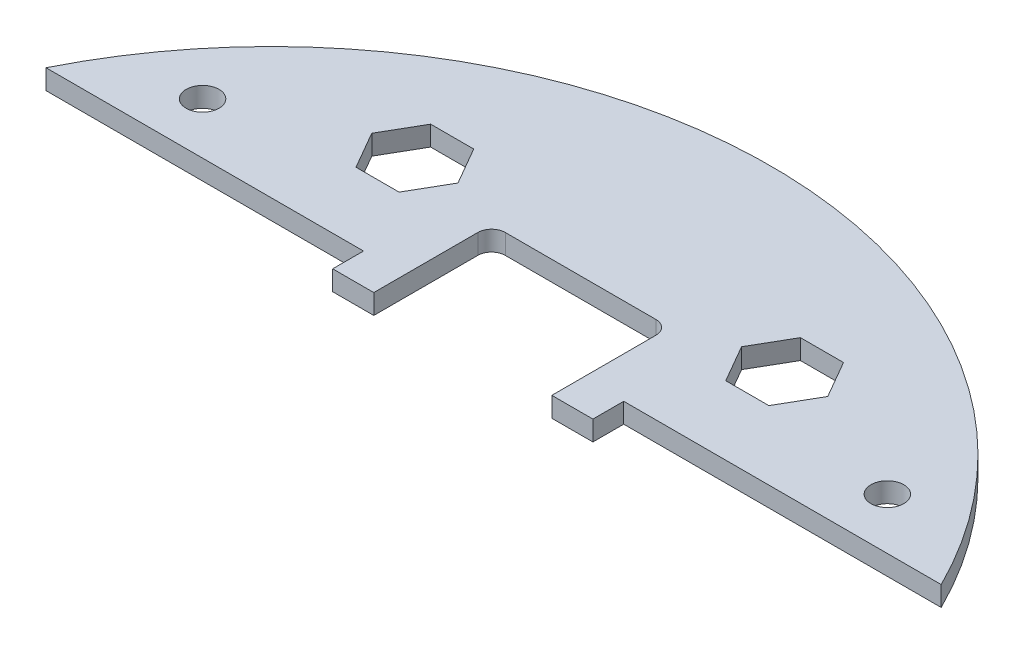
SolidWorks part; units mm, degrees
material "Acrylic (Medium-high impact)"
ref_plane "Front Plane" through (0, 0, 0) normal (0, 0, 1) x (1, 0, 0)
ref_plane "Top Plane" through (0, 0, 0) normal (0, 1, 0) x (1, 0, 0)
ref_plane "Right Plane" through (0, 0, 0) normal (1, 0, 0) x (0, 0, -1)
sketch "Sketch1" plane through (0, 0, 0) normal (0, 1, 0) x (1, 0, 0)
  line L0 (0, -85) -> (-32.7511, -65.2408) construction
  line L1 (0, -85) -> (0, 0) construction
  arc A0 (36.8566, -63.0126) -> (-36.8566, -63.0126) centre (0, 0) ccw
  arc A1 (30.3631, -61.7375) -> (-30.3631, -61.7375) centre (0, -85) ccw
  arc A2 (36.8566, -63.0126) -> (30.3631, -61.7375) centre (34.3322, -58.6967) cw
  arc A3 (-30.3631, -61.7375) -> (-36.8566, -63.0126) centre (-34.3322, -58.6967) cw
  dimension "D1" = 146
  dimension "D2" = 76.5
  dimension "D4" = 5
  dimension "D3" = 85
extrude "Boss-Extrude1" add sketch "Sketch1" along normal blind 2.9
sketch "solenoid placement" plane through (0, 2.9, 0) normal (0, 1, 0) x (1, 0, 0)
  line L4 (-19, -36) -> (19, -36)
  line L5 (-19, 28) -> (-19, -36)
  line L6 (19, 28) -> (-19, 28)
  line L7 (19, -36) -> (19, 28)
  line L8 (-19, -36) -> (19, -36)
  line L9 (-19, 28) -> (-19, -36)
  line L10 (19, 28) -> (-19, 28)
  line L11 (19, -36) -> (19, 28)
  dimension "D1" = 0
extrude "Cut-Extrude1" cut sketch "solenoid placement" against normal through all
sketch "Sketch4" plane through (0, 2.9, 0) normal (0, 1, 0) x (1, 0, 0)
  line L6 (-13, 28) -> (13, 28)
  line L7 (13, 28) -> (13, 43.2)
  line L8 (11, 45.2) -> (-11, 45.2)
  line L9 (-13, 43.2) -> (-13, 28)
  line L10 (-13, 28) -> (13, 28)
  line L11 (13, 28) -> (13, 43.2)
  line L12 (11, 45.2) -> (-11, 45.2)
  line L13 (-13, 43.2) -> (-13, 28)
  arc A4 (13, 43.2) -> (11, 45.2) centre (11, 43.2) ccw
  arc A5 (13, 43.2) -> (11, 45.2) centre (11, 43.2) ccw
  arc A6 (-11, 45.2) -> (-13, 43.2) centre (-11, 43.2) ccw
  arc A7 (-11, 45.2) -> (-13, 43.2) centre (-11, 43.2) ccw
  dimension "D1" = 0
extrude "Cut-Extrude4" cut sketch "Sketch4" against normal through all
sketch "Sketch5" plane through (0, 2.9, 0) normal (0, 1, 0) x (1, 0, 0)
  line L0 (0, 0) -> (0, 73) construction
  line L1 (-20.7069, 48) -> (-23.8534, 53.45)
  line L2 (-23.8534, 53.45) -> (-30.1466, 53.45)
  line L3 (-30.1466, 53.45) -> (-33.2931, 48)
  line L4 (-33.2931, 48) -> (-30.1466, 42.55)
  line L5 (-30.1466, 42.55) -> (-23.8534, 42.55)
  line L6 (-23.8534, 42.55) -> (-20.7069, 48)
  line L7 (23.8534, 42.55) -> (20.7069, 48)
  line L8 (30.1466, 42.55) -> (23.8534, 42.55)
  line L9 (33.2931, 48) -> (30.1466, 42.55)
  line L10 (30.1466, 53.45) -> (33.2931, 48)
  line L11 (23.8534, 53.45) -> (30.1466, 53.45)
  line L12 (20.7069, 48) -> (23.8534, 53.45)
  circle A0 centre (-27, 48) radius 5.45 construction
  circle A2 centre (27, 48) radius 5.45 construction
  arc A3 (36.8566, -63.0126) -> (-36.8566, -63.0126) centre (0, 0) ccw construction
  dimension "D3" = 10.9
extrude "Cut-Extrude5" cut sketch "Sketch5" against normal through all
sketch "Sketch6" plane through (0, 2.9, 0) normal (0, 1, 0) x (1, 0, 0)
  circle A1 centre (40, -40) radius 2.4
  circle A2 centre (40, -40) radius 2.4
  circle A3 centre (-40, -40) radius 2.4
  circle A4 centre (-40, -40) radius 2.4
  circle A5 centre (-50, 40) radius 2.4
  circle A6 centre (-50, 40) radius 2.4
  circle A7 centre (50, 40) radius 2.4
  circle A8 centre (50, 40) radius 2.4
  dimension "D1" = 0
  dimension "D2" = 0
  dimension "D3" = 0
  dimension "D4" = 0
extrude "Cut-Extrude6" cut sketch "Sketch6" against normal through all
sketch "Sketch3" plane through (0, 2.9, 0) normal (0, 1, 0) x (1, 0, 0)
  line L0 (-19, 28) -> (19, 28)
  line L1 (-73, -32.5) -> (73, -32.5)
  line L2 (-73, -32.5) -> (-73, 32.5)
  line L3 (-73, 32.5) -> (-19, 32.5)
  line L4 (73, -32.5) -> (73, 32.5)
  line L5 (-73, -32.5) -> (73, 32.5) construction
  line L6 (-73, 32.5) -> (73, -32.5) construction
  line L7 (19, 28) -> (19, 32.5)
  line L8 (-19, 28) -> (-19, 32.5)
  line L9 (19, 32.5) -> (73, 32.5)
  arc A0 (36.8566, -63.0126) -> (-36.8566, -63.0126) centre (0, 0) ccw construction
  point P0 (0, 0)
  dimension "D1" = 65
extrude "Cut-Extrude3" cut sketch "Sketch3" against normal through all
sketch "Sketch7" plane through (0, 2.9, 0) normal (0, 1, 0) x (1, 0, 0)
  line L4 (5, 0) -> (-5, 0)
  line L5 (5, -62.8025) -> (5, 0)
  line L6 (-5, -62.8025) -> (5, -62.8025)
  line L7 (-5, 0) -> (-5, -62.8025)
  line L8 (5, 0) -> (-5, 0)
  line L9 (5, -62.8025) -> (5, 0)
  line L10 (-5, -62.8025) -> (5, -62.8025)
  line L11 (-5, 0) -> (-5, -62.8025)
  dimension "D1" = 0
extrude "Cut-Extrude7" cut sketch "Sketch7" against normal through all
delete or keep bodies "Body-Delete/Keep 1" type delete bodies bodies 116 117
equation "\"smallPulleyTeeth\"= 15"
equation "\"largePulleyTeeth\"= 30"
equation "\"eighthThick\"= 2.9mm"
equation "\"sixteenthThick\" = 1.7mm"
equation "\"quarterThick\"=6.0mm"
equation "\"OD\" = 146mm"
equation "\"puckAngle\" = 60.5deg"
equation "\"D1@Sketch1\"=\"OD\""
equation "\"puckDiam\" = 76.5mm"
equation "\"D2@Sketch1\"=\"puckDiam\""
equation "\"D1@Boss-Extrude1\"=\"eighthThick\""
equation "\"axlePress\" = 5.9mm"
equation "\"press\" = 0.2mm"
equation "\"wheelClear\" = 0.3mm"
equation "\"10-32clear\" = 4.8mm"
equation "\"6-32clear\" = 3.3mm"
equation "\"8-32clear\" = 4.0mm"
equation "\"wheelHeight\" = 22mm"
equation "\"wheelWell\" = 65mm"
equation "\"D1@Sketch3\"=\"wheelWell\""
equation "\"puckDist\" = 85mm"
equation "\"scoopFillet\" = 5mm"
equation "\"4-40clear\" = 3.0mm"
equation "\"D3@Sketch1\"=\"puckDist\""
equation "\"D4@Sketch1\"=\"scoopFillet\""
